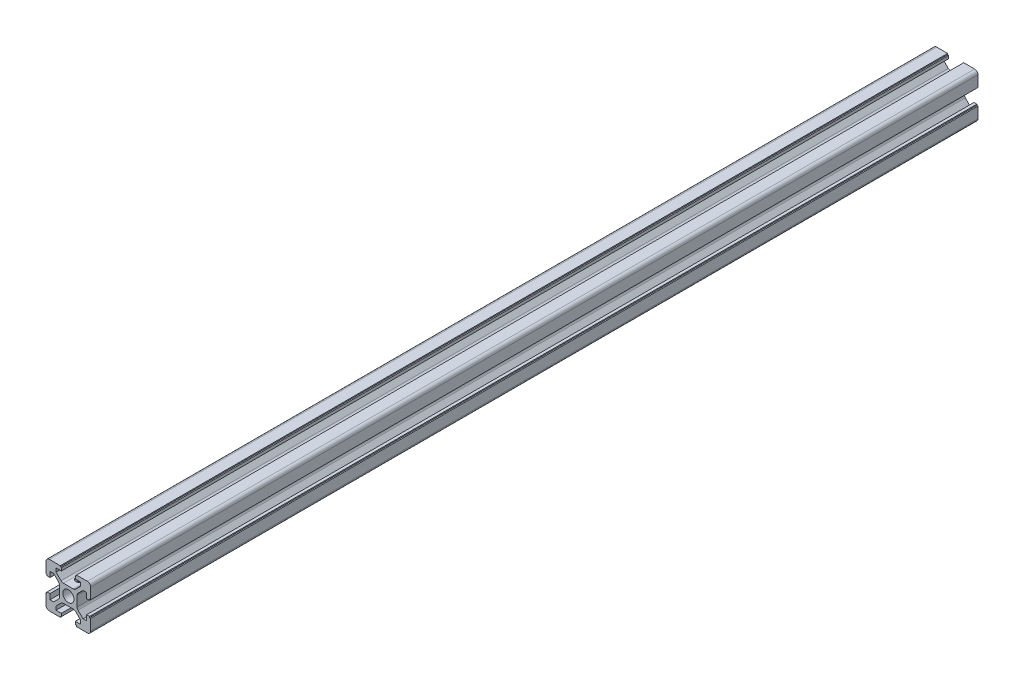
SolidWorks part; units mm, degrees
material "6061 合金"
ref_plane "前视基准面" through (0, 0, 0) normal (0, 0, 1) x (1, 0, 0)
ref_plane "上视基准面" through (0, 0, 0) normal (0, 1, 0) x (1, 0, 0)
ref_plane "右视基准面" through (0, 0, 0) normal (1, 0, 0) x (0, 0, -1)
sketch "草图1" plane through (0, 0, 0) normal (0, 0, 1) x (1, 0, 0)
  line L0 (-6.5607, 5.5) -> (-4.3393, 3.2787)
  line L1 (-3.9, 2.218) -> (-3.9, -2.218)
  line L2 (-4.3393, -3.2787) -> (-6.5607, -5.5)
  line L3 (-6.5607, -5.5) -> (-8.2, -5.5)
  line L4 (-8.2, -5.5) -> (-8.2, -3.1)
  line L5 (-8.2, -3.1) -> (-9.5, -3.1)
  line L6 (-9.5, -3.1) -> (-9.5, -3.6)
  line L7 (-9.5, -3.6) -> (-10, -3.6)
  line L8 (-10, -3.6) -> (-10, -8.5)
  line L9 (-6.5607, 5.5) -> (-8.2, 5.5)
  line L10 (-8.2, 5.5) -> (-8.2, 3.1)
  line L11 (-8.2, 3.1) -> (-9.5, 3.1)
  line L12 (-9.5, 3.1) -> (-9.5, 3.6)
  line L13 (-9.5, 3.6) -> (-10, 3.6)
  line L14 (-10, 3.6) -> (-10, 8.5)
  line L15 (5.5, 6.5607) -> (3.2787, 4.3393)
  line L16 (2.218, 3.9) -> (-2.218, 3.9)
  line L17 (-3.2787, 4.3393) -> (-5.5, 6.5607)
  line L18 (-5.5, 6.5607) -> (-5.5, 8.2)
  line L19 (-5.5, 8.2) -> (-3.1, 8.2)
  line L20 (-3.1, 8.2) -> (-3.1, 9.5)
  line L21 (-3.1, 9.5) -> (-3.6, 9.5)
  line L22 (-3.6, 9.5) -> (-3.6, 10)
  line L23 (-3.6, 10) -> (-8.5, 10)
  line L24 (5.5, 6.5607) -> (5.5, 8.2)
  line L25 (5.5, 8.2) -> (3.1, 8.2)
  line L26 (3.1, 8.2) -> (3.1, 9.5)
  line L27 (3.1, 9.5) -> (3.6, 9.5)
  line L28 (3.6, 9.5) -> (3.6, 10)
  line L29 (3.6, 10) -> (8.5, 10)
  line L30 (6.5607, -5.5) -> (4.3393, -3.2787)
  line L31 (3.9, -2.218) -> (3.9, 2.218)
  line L32 (4.3393, 3.2787) -> (6.5607, 5.5)
  line L33 (6.5607, 5.5) -> (8.2, 5.5)
  line L34 (8.2, 5.5) -> (8.2, 3.1)
  line L35 (8.2, 3.1) -> (9.5, 3.1)
  line L36 (9.5, 3.1) -> (9.5, 3.6)
  line L37 (9.5, 3.6) -> (10, 3.6)
  line L38 (10, 3.6) -> (10, 8.5)
  line L39 (6.5607, -5.5) -> (8.2, -5.5)
  line L40 (8.2, -5.5) -> (8.2, -3.1)
  line L41 (8.2, -3.1) -> (9.5, -3.1)
  line L42 (9.5, -3.1) -> (9.5, -3.6)
  line L43 (9.5, -3.6) -> (10, -3.6)
  line L44 (10, -3.6) -> (10, -8.5)
  line L45 (-5.5, -6.5607) -> (-3.2787, -4.3393)
  line L46 (-2.218, -3.9) -> (2.218, -3.9)
  line L47 (3.2787, -4.3393) -> (5.5, -6.5607)
  line L48 (5.5, -6.5607) -> (5.5, -8.2)
  line L49 (5.5, -8.2) -> (3.1, -8.2)
  line L50 (3.1, -8.2) -> (3.1, -9.5)
  line L51 (3.1, -9.5) -> (3.6, -9.5)
  line L52 (3.6, -9.5) -> (3.6, -10)
  line L53 (3.6, -10) -> (8.5, -10)
  line L54 (-5.5, -6.5607) -> (-5.5, -8.2)
  line L55 (-5.5, -8.2) -> (-3.1, -8.2)
  line L56 (-3.1, -8.2) -> (-3.1, -9.5)
  line L57 (-3.1, -9.5) -> (-3.6, -9.5)
  line L58 (-3.6, -9.5) -> (-3.6, -10)
  line L59 (-3.6, -10) -> (-8.5, -10)
  line L60 (0, 0) -> (-3.9, 2.8393) construction
  line L61 (0, 0) -> (2.8393, 3.9) construction
  arc A0 (4.3393, -3.2787) -> (3.9, -2.218) centre (5.4, -2.218) cw
  arc A1 (3.9, 2.218) -> (4.3393, 3.2787) centre (5.4, 2.218) cw
  arc A2 (3.2787, 4.3393) -> (2.218, 3.9) centre (2.218, 5.4) cw
  arc A3 (-2.218, 3.9) -> (-3.2787, 4.3393) centre (-2.218, 5.4) cw
  arc A4 (-4.3393, 3.2787) -> (-3.9, 2.218) centre (-5.4, 2.218) cw
  arc A5 (-3.9, -2.218) -> (-4.3393, -3.2787) centre (-5.4, -2.218) cw
  arc A6 (2.218, -3.9) -> (3.2787, -4.3393) centre (2.218, -5.4) cw
  arc A7 (-3.2787, -4.3393) -> (-2.218, -3.9) centre (-2.218, -5.4) cw
  arc A8 (-10, -8.5) -> (-8.5, -10) centre (-8.5, -8.5) ccw
  arc A9 (10, -8.5) -> (8.5, -10) centre (8.5, -8.5) cw
  arc A10 (8.5, 10) -> (10, 8.5) centre (8.5, 8.5) cw
  arc A11 (-10, 8.5) -> (-8.5, 10) centre (-8.5, 8.5) cw
  circle A12 centre (0, 0) radius 2.5
  point P27 (-3.9, 0)
  point P75 (2.8393, 3.9)
  dimension "D12" = 1.5
  dimension "D13" = 5
  dimension "D2" = 20
  dimension "D3" = 7.2
  dimension "D4" = 6.2
  dimension "D5" = 7.8
  dimension "D6" = 45
  dimension "D7" = 1.5
  dimension "D8" = 11
  dimension "D9" = 1.8
  dimension "D10" = 0.5
  dimension "D11" = 3.1
  dimension "D1" = 4
extrude "凸台-拉伸1" add sketch "草图1" along normal mid plane 397
sketch "草图3" plane through (0, 10, 0) normal (0, 1, 0) x (1, 0, 0)
  line L0 (2.218, 198.5) -> (-2.218, 198.5) construction
  line L1 (-3.6, -198.5) -> (-8.5, -198.5) construction
  circle A0 centre (0, 193.5) radius 1.6
  circle A2 centre (0, 173.5) radius 1.6
  circle A3 centre (0, -193.5) radius 1.6
  circle A4 centre (0, -173.5) radius 1.6
  dimension "D1" = 3.2
  dimension "D2" = 20
  dimension "D3" = 5
  dimension "D4" = 20
  dimension "D5" = 5
extrude "切除-拉伸1" cut sketch "草图3" against normal through all
